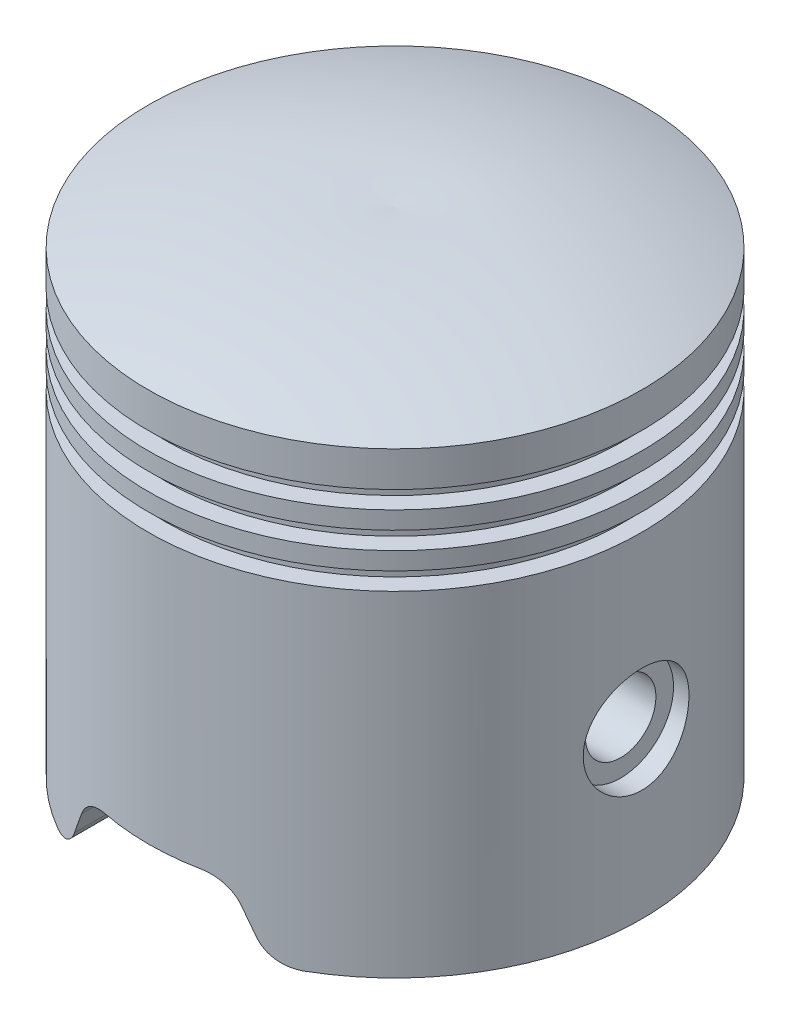
SolidWorks part; units mm, degrees
ref_plane "Front Plane" through (0, 0, 0) normal (0, 0, 1) x (1, 0, 0)
ref_plane "Top Plane" through (0, 0, 0) normal (0, 1, 0) x (1, 0, 0)
ref_plane "Right Plane" through (0, 0, 0) normal (1, 0, 0) x (0, 0, -1)
sketch "Sketch1" plane through (0, 0, 0) normal (0, 0, 1) x (1, 0, 0)
  line L0 (0, 0) -> (0, 28023.0375) construction
  line L1 (0, 0) -> (-28023.0375, 0) construction
  line L3 (35, 65) -> (35, 60)
  line L4 (35, 60) -> (32.5, 60)
  line L5 (32.5, 60) -> (32.5, 57.5)
  line L6 (32.5, 57.5) -> (35, 57.5)
  line L7 (35, 57.5) -> (35, 55)
  line L8 (35, 55) -> (32.5, 55)
  line L9 (32.5, 55) -> (32.5, 52.5)
  line L10 (32.5, 52.5) -> (35, 52.5)
  line L11 (35, 52.5) -> (35, 50)
  line L12 (35, 50) -> (32.5, 50)
  line L13 (32.5, 50) -> (32.5, 47.5)
  line L14 (32.5, 47.5) -> (35, 47.5)
  line L15 (35, 47.5) -> (35, 0)
  line L18 (0, 63.9391) -> (26.5, 60.1534)
  line L19 (26.5, 60.1534) -> (26.5, 60.1534)
  line L20 (26.5, 60.1534) -> (26.5, 60.1534)
  line L21 (26.5, 60.1534) -> (26.5, 56.25)
  line L22 (26.5, 56.25) -> (26.5, 56.25)
  line L23 (26.5, 56.25) -> (26.5, 56.25)
  line L24 (26.5, 56.25) -> (26.5, 56.25)
  line L25 (26.5, 56.25) -> (26.5, 51.25)
  line L26 (26.5, 51.25) -> (26.5, 51.25)
  line L27 (26.5, 51.25) -> (26.5, 51.25)
  line L28 (26.5, 51.25) -> (26.5, 51.25)
  line L29 (26.5, 51.25) -> (26.5, 41.5)
  line L30 (26.5, 41.5) -> (29, 41.5)
  line L31 (29, 41.5) -> (29, 0)
  line L32 (0, 70) -> (0, 63.9391)
  line L33 (29, 0) -> (35, 0)
  line L34 (-0.8485, 64.0603) -> (26.5, 60.1534) construction
  line L35 (0, 70) -> (35, 65) construction
  arc A0 (0, 70) -> (35, 65) centre (5.742, -14.8058) cw
  point P22 (26.5, 60.1534)
  point P37 (0, 0)
  point P39 (26.5, 60.1534)
  dimension "D12" = 85
  dimension "D1" = 35
  dimension "D2" = 6
  dimension "D3" = 5
  dimension "D4" = 5
  dimension "D5" = 2.5
  dimension "D6" = 2.5
  dimension "D7" = 2.5
  dimension "D8" = 2.5
  dimension "D9" = 2.5
  dimension "D10" = 2.5
  dimension "D11" = 65
revolve "Revolve1" add sketch "Sketch1" angle 360 about L0
sketch "Sketch2" plane through (0, 0, 0) normal (0, 0, 1) x (1, 0, 0)
  line L0 (0, 0) -> (0, 50000) construction
  line L1 (-35, 0) -> (35, 0) construction
  line L3 (-10, 9.2145) -> (10, 9.2145)
  line L6 (0.5774, -4.9208) -> (0, -4.6515)
  line L7 (-10, 9.2145) -> (-14.2968, 0)
  line L8 (-14.2968, 0) -> (-8.3313, -4.9208)
  line L9 (-8.3313, -4.9208) -> (0.5774, -4.9208)
  line L10 (14.2968, -4.9208) -> (14.2968, 0)
  line L11 (14.2968, 0) -> (10, 9.2145)
  line L12 (0.5774, -4.9208) -> (14.2968, -4.9208)
  point P4 (0, 0)
  dimension "D1" = 20
  dimension "D2" = 10
  dimension "D3" = 25
  dimension "D4" = 25
extrude "Cut-Extrude1" cut sketch "Sketch2" against normal mid plane 100 contours L9 L0 L3 L7 L8 | L0 L6 L12 L10 L11 L3
fillet "Fillet1" radius 5 8 edges at (14.2968, 0, -28.5889) (14.2968, 0, 28.5889) (10, 9.2145, 30.3812) (10, 9.2145, -30.3812) (-14.2968, 0, 28.5889) (-14.2968, 0, -28.5889) (-10, 9.2145, 30.3812) (-10, 9.2145, -30.3812)
ref_plane "Plane1" through (-35, 0, 0) normal (-1, 0, 0) x (0, 0, 1)
sketch "Sketch4" plane through (-35, 0, 0) normal (-1, 0, 0) x (0, 0, 1)
  circle A0 centre (0, 23.3127) radius 7.5
  dimension "D1" = 15
extrude "Cut-Extrude2" cut sketch "Sketch4" against normal blind 3
sketch "Sketch6" plane through (-32, 0, 0) normal (-1, 0, 0) x (0, 0, 1)
  circle A0 centre (0, 23.3127) radius 5
  dimension "D1" = 10
extrude "Cut-Extrude3" cut sketch "Sketch6" against normal blind 21
mirror "Mirror1" about plane through (0, 0, 0) normal (1, 0, 0) of "Cut-Extrude3", "Cut-Extrude2"
sketch "Sketch7" plane through (32, 0, 0) normal (1, 0, 0) x (0, 0, -1)
  circle A0 centre (0, 23.3127) radius 6
  dimension "D1" = 12
extrude "Boss-Extrude1" add sketch "Sketch7" against normal blind 62
sketch "Sketch8" plane through (32, 0, 0) normal (1, 0, 0) x (0, 0, -1)
  circle A0 centre (0, 23.3127) radius 5
  dimension "D1" = 10
extrude "Cut-Extrude4" cut sketch "Sketch8" against normal blind 100
